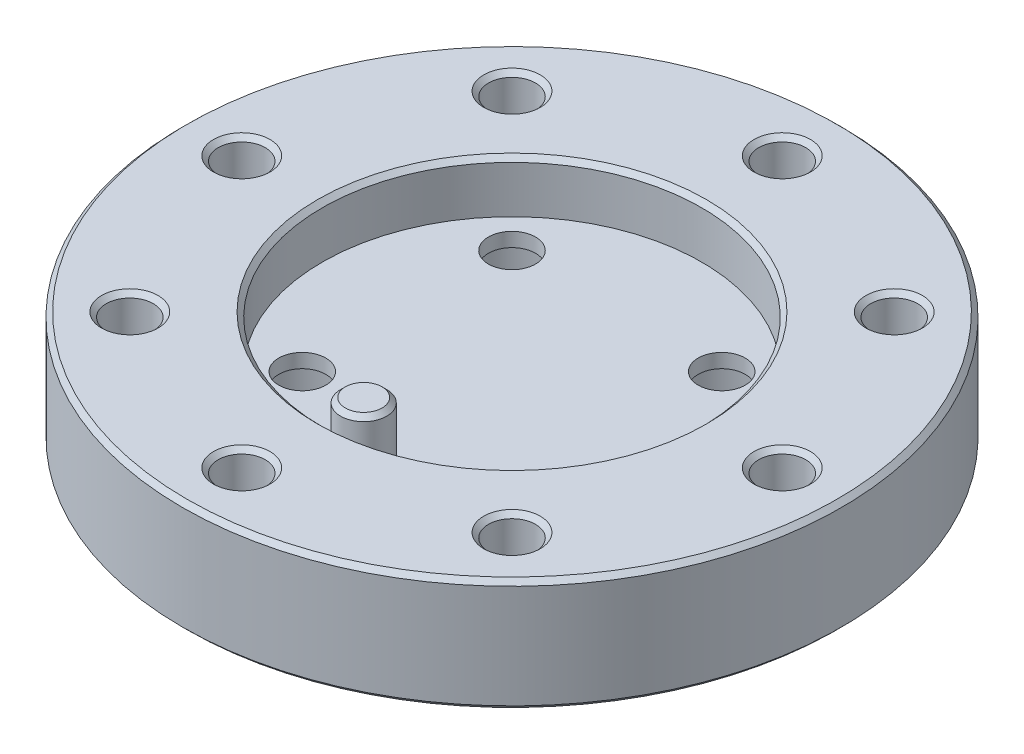
SolidWorks part; units mm, degrees
ref_plane "Front Plane" through (0, 0, 0) normal (0, 0, 1) x (1, 0, 0)
ref_plane "Top Plane" through (0, 0, 0) normal (0, 1, 0) x (1, 0, 0)
ref_plane "Right Plane" through (0, 0, 0) normal (1, 0, 0) x (0, 0, -1)
sketch "Sketch1" plane through (0, 0, 0) normal (0, 1, 0) x (1, 0, 0)
  circle A0 centre (0, 0) radius 35
  dimension "D1" = 70
extrude "Boss-Extrude1" add sketch "Sketch1" along normal blind 12
sketch "Sketch2" plane through (0, 12, 0) normal (0, 1, 0) x (1, 0, 0)
  circle A0 centre (0, 0) radius 20.15
  dimension "D1" = 40.3
extrude "Cut-Extrude1" cut sketch "Sketch2" against normal blind 5.5
sketch "Sketch3" plane through (0, 6.5, 0) normal (0, 1, 0) x (1, 0, 0)
  line L0 (0, 0) -> (0, -32.8028) construction
  circle A0 centre (0, -15.75) radius 2.45
  dimension "D2" = 4.9
  dimension "D1" = 15.75
extrude "Boss-Extrude2" add sketch "Sketch3" along normal up to surface (5.5 mm away) up to face at (0, 12, 20.15)
sketch "Sketch4" plane through (0, 6.5, 0) normal (0, 1, 0) x (1, 0, 0)
  line L0 (0, 0) -> (0, 33.8827) construction
  line L1 (0, 0) -> (32.4771, 32.4771) construction
  circle A0 centre (11.1369, 11.1369) radius 2.5
  circle A1 centre (11.1369, -11.1369) radius 2.5
  circle A2 centre (-11.1369, -11.1369) radius 2.5
  circle A3 centre (-11.1369, 11.1369) radius 2.5
  point P14 (0, 0)
  dimension "D3" = 5
  dimension "D1" = 45
  dimension "D2" = 15.75
  dimension "D4" = 4
extrude "Cut-Extrude2" cut sketch "Sketch4" against normal through all
sketch "Sketch5" plane through (0, 0, 0) normal (0, -1, 0) x (1, 0, 0)
  circle A1 centre (11.1369, -11.1369) radius 5.5
  circle A2 centre (11.1369, 11.1369) radius 5.5
  circle A3 centre (11.1369, 11.1369) radius 5.5
  circle A4 centre (-11.1369, -11.1369) radius 5.5
  circle A5 centre (-11.1369, 11.1369) radius 5.5
  point P11 (0, 0)
  dimension "D1" = 3
  dimension "D2" = 4
extrude "Cut-Extrude3" cut sketch "Sketch5" against normal blind 5
sketch "Sketch6" plane through (0, 0, 0) normal (0, -1, 0) x (1, 0, 0)
  line L0 (0, 0) -> (50.0816, 0) construction
  circle A0 centre (28.702, 0) radius 2.5
  circle A1 centre (20.2954, -20.2954) radius 2.5
  circle A2 centre (0, -28.702) radius 2.5
  circle A3 centre (-20.2954, -20.2954) radius 2.5
  circle A4 centre (-28.702, 0) radius 2.5
  circle A5 centre (-20.2954, 20.2954) radius 2.5
  circle A6 centre (0, 28.702) radius 2.5
  circle A7 centre (20.2954, 20.2954) radius 2.5
  point P21 (0, 0)
  dimension "D1" = 5
  dimension "D2" = 28.702
  dimension "D3" = 8
extrude "Cut-Extrude4" cut sketch "Sketch6" against normal through all
chamfer "Chamfer1" distance 0.5 angle 45 13 edges at (0, 0, 35) (11.1369, 0, 5.6369) (11.1369, 0, -16.6369) (-11.1369, 0, -16.6369) (-11.1369, 0, 5.6369) (20.2954, 0, 17.7954) (0, 0, 26.202) (-20.2954, 0, 17.7954) (-28.702, 0, -2.5) (-20.2954, 0, -22.7954) (0, 0, -31.202) (20.2954, 0, -22.7954) (28.702, 0, -2.5)
chamfer "Chamfer2" distance 0.5 angle 45 10 edges at (0, 12, 35) (0, 12, 20.15) (20.2954, 12, 17.7954) (0, 12, 26.202) (-20.2954, 12, 17.7954) (-28.702, 12, -2.5) (-20.2954, 12, -22.7954) (0, 12, -31.202) (20.2954, 12, -22.7954) (28.702, 12, -2.5)
chamfer "Chamfer3" distance 0.5 angle 45 1 edges at (0, 12, 18.2)
